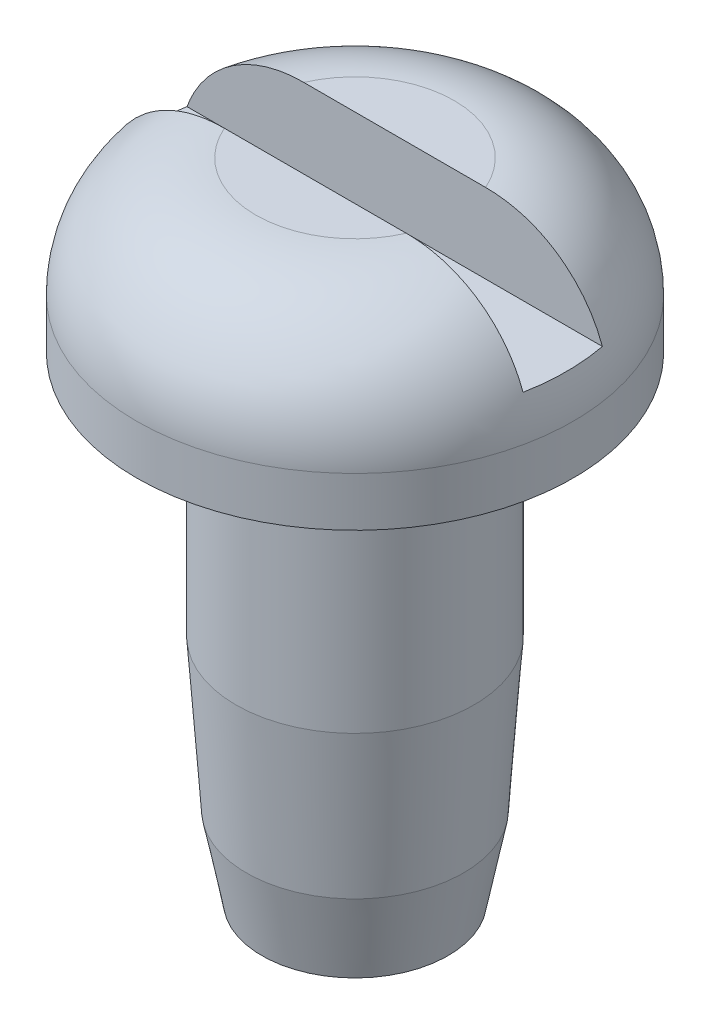
SolidWorks part; units mm, degrees
ref_plane "Спереди" through (0, 0, 0) normal (0, 0, 1) x (1, 0, 0)
ref_plane "Сверху" through (0, 0, 0) normal (0, 1, 0) x (1, 0, 0)
ref_plane "Справа" through (0, 0, 0) normal (1, 0, 0) x (0, 0, -1)
sketch "Эскиз1" plane through (0, 0, 0) normal (0, 0, 1) x (1, 0, 0)
  line L0 (0, 0) -> (0, 8.12)
  line L1 (0, 8.12) -> (1.25, 8.12)
  line L2 (2.75, 6.62) -> (2.75, 6)
  line L3 (2.75, 6) -> (1.5, 6)
  line L4 (1.5, 6) -> (1.5, 2.9)
  line L5 (1.5, 2.9) -> (1.3671, 1)
  line L6 (1.1728, 0) -> (0, 0)
  line L7 (1.3671, 1) -> (1.1728, 0)
  arc A0 (1.25, 8.12) -> (2.75, 6.62) centre (1.25, 6.62) cw
  dimension "D5" = 1.5
  dimension "D1" = 1.5
  dimension "D2" = 2.12
  dimension "D3" = 6
  dimension "D4" = 2.75
  dimension "D6" = 2.9
  dimension "D7" = 4
  dimension "D8" = 7
  dimension "D9" = 1
revolve "Повернуть1" add sketch "Эскиз1" angle 360 about L0
sketch "Эскиз2" plane through (0, 0, 0) normal (1, 0, 0) x (0, 0, -1)
  line L0 (0, 7.12) -> (0, 0) construction
  line L1 (-0.5, 8.12) -> (0.5, 8.12)
  line L2 (-0.5, 8.12) -> (-0.5, 7.12)
  line L3 (-0.5, 7.12) -> (0.5, 7.12)
  line L4 (0.5, 8.12) -> (0.5, 7.12)
  line L5 (-1.1728, 0) -> (1.1728, 0) construction
  line L6 (1.25, 8.12) -> (-1.25, 8.12) construction
  dimension "D1" = 1
  dimension "D2" = 1
extrude "Вырез-Вытянуть1" cut sketch "Эскиз2" against normal mid plane 10
